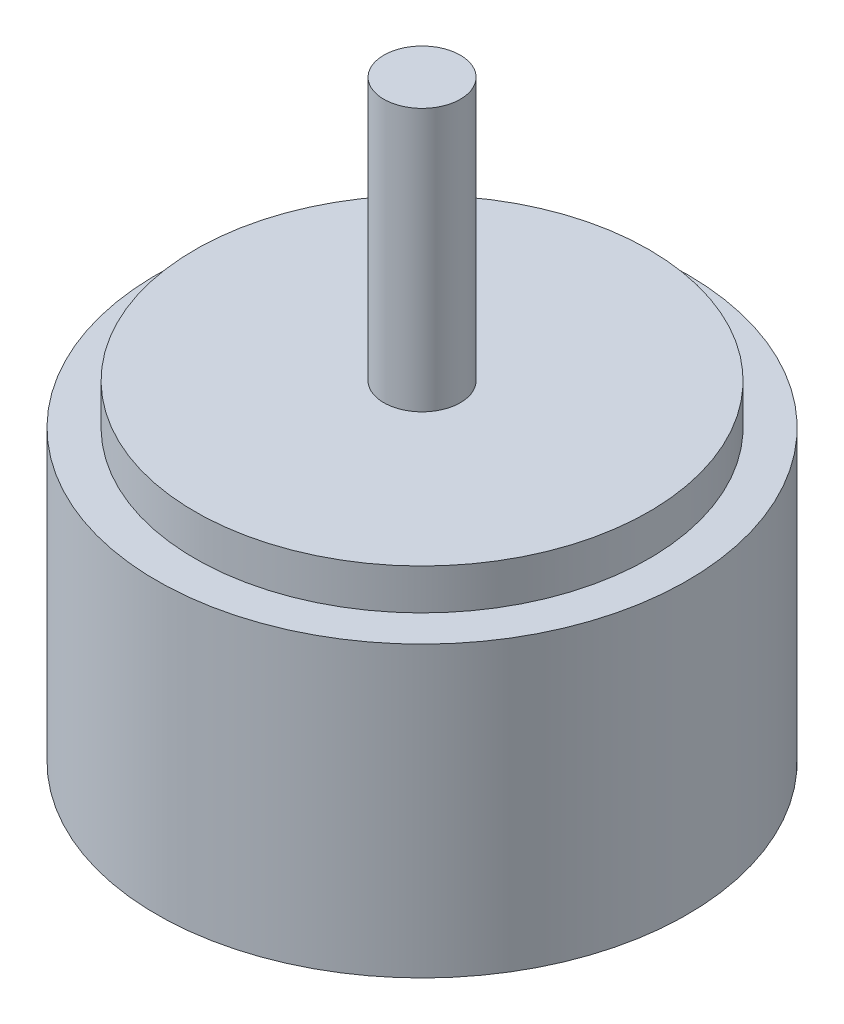
SolidWorks part; units mm, degrees
ref_plane "Front Plane" through (0, 0, 0) normal (0, 0, 1) x (1, 0, 0)
ref_plane "Top Plane" through (0, 0, 0) normal (0, 1, 0) x (1, 0, 0)
ref_plane "Right Plane" through (0, 0, 0) normal (1, 0, 0) x (0, 0, -1)
sketch "Sketch1" plane through (0, 0, 0) normal (0, 0, 1) x (1, 0, 0)
  line L0 (0, 0) -> (0, 19404.7876) construction
  line L1 (0, 0) -> (11.1, 0)
  line L2 (11.1, 0) -> (11.1, 12.1)
  line L3 (11.1, 12.1) -> (9.5, 12.1)
  line L4 (9.5, 12.1) -> (9.5, 13.8)
  line L5 (9.5, 13.8) -> (1.6, 13.8)
  line L6 (1.6, 13.8) -> (1.6, 24.8)
  line L7 (1.6, 24.8) -> (0, 24.8)
  line L8 (0, 24.8) -> (0, 0)
  dimension "D1" = 22.2
  dimension "D2" = 19
  dimension "D3" = 3.2
  dimension "D4" = 12.1
  dimension "D5" = 13.8
  dimension "D6" = 11
revolve "Revolve1" add sketch "Sketch1" angle 360 about L0
